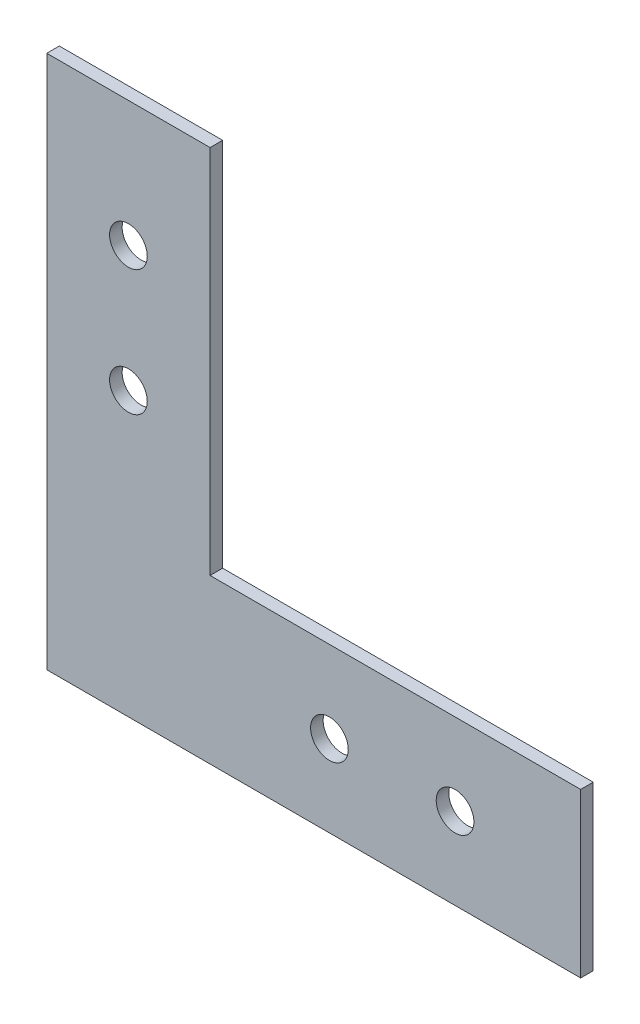
SolidWorks part; units mm, degrees
ref_plane "前视基准面" through (0, 0, 0) normal (0, 0, 1) x (1, 0, 0)
ref_plane "上视基准面" through (0, 0, 0) normal (0, 1, 0) x (1, 0, 0)
ref_plane "右视基准面" through (0, 0, 0) normal (1, 0, 0) x (0, 0, -1)
sketch "草图1" plane through (0, 0, 0) normal (0, 0, 1) x (1, 0, 0)
  line L0 (-13, -42.5) -> (24.0105, -5.4895) construction
  line L1 (-13, -42.5) -> (13, -42.5)
  line L2 (-13, -42.5) -> (-13, 42.5)
  line L3 (-13, 42.5) -> (13, 42.5)
  line L4 (13, -42.5) -> (13, 42.5)
  line L5 (-13, -42.5) -> (13, 42.5) construction
  line L6 (-13, 42.5) -> (13, -42.5) construction
  point P0 (0, 0)
  dimension "D1" = 26
  dimension "D2" = 85
  dimension "D3" = 45
extrude "凸台-拉伸1" add sketch "草图1" along normal blind 2
ref_plane "基准面1" through (14.75, -14.75, 0) normal (0.7071, -0.7071, 0) x (-0.7071, -0.7071, 0)
mirror "镜向1" about plane through (14.75, -14.75, 0) normal (0.7071, -0.7071, 0) of "凸台-拉伸1"
sketch "草图2" plane through (0, 0, 2) normal (0, 0, 1) x (1, 0, 0)
  line L0 (13, 42.5) -> (-13, 42.5) construction
  circle A0 centre (0, 22.5) radius 3
  circle A1 centre (0, 2.5) radius 3
  dimension "D1" = 20
  dimension "D2" = 6
  dimension "D3" = 20
extrude "切除-拉伸1" cut sketch "草图2" against normal blind 10
ref_plane "基准面2" through (14.75, -14.75, 0) normal (0.7071, -0.7071, 0) x (0, 0, -1)
mirror "镜向2" about plane through (14.75, -14.75, 0) normal (0.7071, -0.7071, 0) of "切除-拉伸1"
